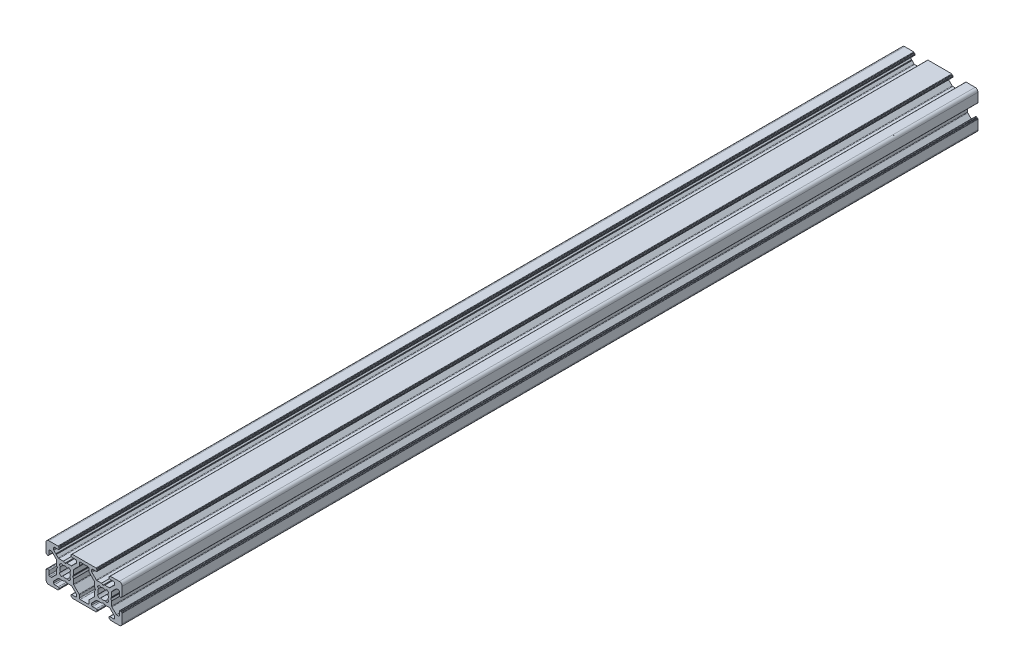
SolidWorks part; units mm, degrees
material "3.1355 (EN-AW 2024)"
ref_plane "Спереди" through (0, 0, 0) normal (0, 0, 1) x (1, 0, 0)
ref_plane "Сверху" through (0, 0, 0) normal (0, 1, 0) x (1, 0, 0)
ref_plane "Справа" through (0, 0, 0) normal (1, 0, 0) x (0, 0, -1)
sketch "Model" plane through (0, 0, 0) normal (0, 0, 1) x (1, 0, 0)
  line L0 (8.0901, 2.9922) -> (8.7418, 2.4453)
  line L1 (11.2582, 2.4453) -> (11.9099, 2.9922)
  line L2 (12.9896, 1.9139) -> (12.4453, 1.2582)
  line L3 (12.4453, -1.2582) -> (12.9896, -1.9139)
  line L4 (11.9099, -2.9922) -> (11.2582, -2.4453)
  line L5 (8.7418, -2.4453) -> (8.0901, -2.9922)
  line L6 (7.0104, -1.9139) -> (7.5547, -1.2582)
  line L7 (7.5547, 1.2582) -> (7.0104, 1.9139)
  line L8 (-7.0104, 1.9139) -> (-7.5547, 1.2582)
  line L9 (-7.5547, -1.2582) -> (-7.0104, -1.9139)
  line L10 (-8.0901, -2.9922) -> (-8.7418, -2.4453)
  line L11 (-11.2582, -2.4453) -> (-11.9099, -2.9922)
  line L12 (-12.9896, -1.9139) -> (-12.4453, -1.2582)
  line L13 (-12.4453, 1.2582) -> (-12.9896, 1.9139)
  line L14 (-11.9099, 2.9922) -> (-11.2582, 2.4453)
  line L15 (-8.7418, 2.4453) -> (-8.0901, 2.9922)
  line L16 (5.5267, 0.8538) -> (5.9619, 0.1)
  line L17 (5.9619, -0.1) -> (5.5267, -0.8538)
  line L18 (5.4999, -0.9538) -> (5.4999, -3.2324)
  line L19 (5.3534, -3.586) -> (2.6465, -6.2929)
  line L20 (2.5, -6.6464) -> (2.5, -8)
  line L21 (2, -8.5) -> (-2, -8.5)
  line L22 (-2.5, -8) -> (-2.5, -6.6464)
  line L23 (-2.6464, -6.2929) -> (-5.3535, -3.5858)
  line L24 (-5.5, -3.2322) -> (-5.5, -0.9536)
  line L25 (-5.5268, -0.8536) -> (-5.9619, -0.1)
  line L26 (-5.9619, 0.1) -> (-5.5268, 0.8536)
  line L27 (-5.5, 0.9536) -> (-5.5, 3.2322)
  line L28 (-5.3535, 3.5858) -> (-2.6464, 6.2929)
  line L29 (-2.5, 6.6464) -> (-2.5, 8)
  line L30 (-2, 8.5) -> (2, 8.5)
  line L31 (2.5, 8) -> (2.5, 6.6464)
  line L32 (2.6465, 6.2929) -> (5.3534, 3.586)
  line L33 (5.4999, 3.2324) -> (5.4999, 0.9538)
  line L34 (-14.7904, 5.7096) -> (-14.8421, 5.9028)
  line L35 (-14.8421, 5.9028) -> (-15.8536, 6.9142)
  line L36 (-16, 7.2678) -> (-16, 8)
  line L37 (-15.5, 8.5) -> (-13.6, 8.5)
  line L38 (-13.1, 9) -> (-13.1, 9.3)
  line L39 (-13.3, 9.5) -> (-13.35, 9.5)
  line L40 (-13.55, 9.7) -> (-13.55, 9.8)
  line L41 (-13.75, 10) -> (-18.5, 10)
  line L42 (-20, 8.5) -> (-20, 3.75)
  line L43 (-19.8, 3.55) -> (-19.7, 3.55)
  line L44 (-19.5, 3.35) -> (-19.5, 3.3)
  line L45 (-19.3, 3.1) -> (-19, 3.1)
  line L46 (-18.5, 3.6) -> (-18.5, 5.5)
  line L47 (-18, 6) -> (-17.2678, 6)
  line L48 (-16.9142, 5.8536) -> (-14.6464, 3.5858)
  line L49 (-14.5, 3.2322) -> (-14.5, 0.9536)
  line L50 (-14.4732, 0.8536) -> (-14.0381, 0.1)
  line L51 (-14.0381, -0.1) -> (-14.4732, -0.8536)
  line L52 (-14.5, -0.9536) -> (-14.5, -3.2322)
  line L53 (-14.6464, -3.5858) -> (-16.9142, -5.8536)
  line L54 (-17.2678, -6) -> (-18, -6)
  line L55 (-18.5, -5.5) -> (-18.5, -3.6)
  line L56 (-19, -3.1) -> (-19.3, -3.1)
  line L57 (-19.5, -3.3) -> (-19.5, -3.35)
  line L58 (-19.7, -3.55) -> (-19.8, -3.55)
  line L59 (-20, -3.75) -> (-20, -8.5)
  line L60 (-18.5, -10) -> (-13.75, -10)
  line L61 (-13.55, -9.8) -> (-13.55, -9.7)
  line L62 (-13.35, -9.5) -> (-13.3, -9.5)
  line L63 (-13.1, -9.3) -> (-13.1, -9)
  line L64 (-13.6, -8.5) -> (-15.5, -8.5)
  line L65 (-16, -8) -> (-16, -7.2678)
  line L66 (-15.8536, -6.9142) -> (-13.5858, -4.6464)
  line L67 (-13.2322, -4.5) -> (-10.9536, -4.5)
  line L68 (-10.8536, -4.4732) -> (-10.1, -4.0381)
  line L69 (-9.9, -4.0381) -> (-9.1464, -4.4732)
  line L70 (-9.0464, -4.5) -> (-6.7678, -4.5)
  line L71 (-6.4142, -4.6464) -> (-4.1464, -6.9142)
  line L72 (-4, -7.2678) -> (-4, -8)
  line L73 (-4.5, -8.5) -> (-6.4, -8.5)
  line L74 (-6.9, -9) -> (-6.9, -9.3)
  line L75 (-6.7, -9.5) -> (-6.65, -9.5)
  line L76 (-6.45, -9.7) -> (-6.45, -9.8)
  line L77 (-6.25, -10) -> (6.25, -10)
  line L78 (6.45, -9.8) -> (6.45, -9.7)
  line L79 (6.65, -9.5) -> (6.7, -9.5)
  line L80 (6.9, -9.3) -> (6.9, -9)
  line L81 (6.4, -8.5) -> (4.5, -8.5)
  line L82 (4, -8) -> (4, -7.2678)
  line L83 (4.1464, -6.9142) -> (6.4142, -4.6464)
  line L84 (6.7678, -4.5) -> (9.0464, -4.5)
  line L85 (9.1464, -4.4732) -> (9.9, -4.0381)
  line L86 (10.1, -4.0381) -> (10.8536, -4.4732)
  line L87 (10.9536, -4.5) -> (13.2322, -4.5)
  line L88 (13.5858, -4.6464) -> (15.8536, -6.9142)
  line L89 (16, -7.2678) -> (16, -8)
  line L90 (15.5, -8.5) -> (13.6, -8.5)
  line L91 (13.1, -9) -> (13.1, -9.3)
  line L92 (13.3, -9.5) -> (13.35, -9.5)
  line L93 (13.55, -9.7) -> (13.55, -9.8)
  line L94 (13.75, -10) -> (18.5, -10)
  line L95 (20, -8.5) -> (20, -3.75)
  line L96 (19.8, -3.55) -> (19.7, -3.55)
  line L97 (19.5, -3.35) -> (19.5, -3.3)
  line L98 (19.3, -3.1) -> (19, -3.1)
  line L99 (18.5, -3.6) -> (18.5, -5.5)
  line L100 (18, -6) -> (17.2678, -6)
  line L101 (16.9142, -5.8536) -> (14.6464, -3.5858)
  line L102 (14.5, -3.2322) -> (14.5, -0.9536)
  line L103 (14.4732, -0.8536) -> (14.0381, -0.1)
  line L104 (14.0381, 0.1) -> (14.4732, 0.8536)
  line L105 (14.5, 0.9536) -> (14.5, 3.2322)
  line L106 (14.6464, 3.5858) -> (16.9142, 5.8536)
  line L107 (17.2678, 6) -> (18, 6)
  line L108 (18.5, 5.5) -> (18.5, 3.6)
  line L109 (19, 3.1) -> (19.3, 3.1)
  line L110 (19.5, 3.3) -> (19.5, 3.35)
  line L111 (19.7, 3.55) -> (19.8, 3.55)
  line L112 (20, 3.75) -> (20, 8.5)
  line L113 (18.5, 10) -> (13.75, 10)
  line L114 (13.55, 9.8) -> (13.55, 9.7)
  line L115 (13.35, 9.5) -> (13.3, 9.5)
  line L116 (13.1, 9.3) -> (13.1, 9)
  line L117 (13.6, 8.5) -> (15.5, 8.5)
  line L118 (16, 8) -> (16, 7.2678)
  line L119 (15.8536, 6.9142) -> (13.5858, 4.6464)
  line L120 (13.2322, 4.5) -> (10.9536, 4.5)
  line L121 (10.8536, 4.4732) -> (10.1, 4.0381)
  line L122 (9.9, 4.0381) -> (9.1464, 4.4732)
  line L123 (9.0464, 4.5) -> (6.7678, 4.5)
  line L124 (6.4142, 4.6464) -> (4.1464, 6.9142)
  line L125 (4, 7.2678) -> (4, 8)
  line L126 (4.5, 8.5) -> (6.4, 8.5)
  line L127 (6.9, 9) -> (6.9, 9.3)
  line L128 (6.7, 9.5) -> (6.65, 9.5)
  line L129 (6.45, 9.7) -> (6.45, 9.8)
  line L130 (6.25, 10) -> (-6.25, 10)
  line L131 (-6.45, 9.8) -> (-6.45, 9.7)
  line L132 (-6.65, 9.5) -> (-6.7, 9.5)
  line L133 (-6.9, 9.3) -> (-6.9, 9)
  line L134 (-6.4, 8.5) -> (-4.5, 8.5)
  line L135 (-4, 8) -> (-4, 7.2678)
  line L136 (-4.1464, 6.9142) -> (-6.4142, 4.6464)
  line L137 (-6.7678, 4.5) -> (-9.0464, 4.5)
  line L138 (-9.1464, 4.4732) -> (-9.9, 4.0381)
  line L139 (-10.1, 4.0381) -> (-10.8536, 4.4732)
  line L140 (-10.9536, 4.5) -> (-13.2322, 4.5)
  line L141 (-13.5858, 4.6464) -> (-14.5972, 5.6579)
  line L142 (-14.5972, 5.6579) -> (-14.7904, 5.7096)
  arc A0 (8.0901, 2.9922) -> (7.0104, 1.9139) centre (10, 0) ccw
  arc A1 (11.2582, 2.4453) -> (8.7418, 2.4453) centre (10, 0) ccw
  arc A2 (12.9896, 1.9139) -> (11.9099, 2.9922) centre (10, 0) ccw
  arc A3 (12.4453, -1.2582) -> (12.4453, 1.2582) centre (10, 0) ccw
  arc A4 (11.9099, -2.9922) -> (12.9896, -1.9139) centre (10, 0) ccw
  arc A5 (8.7418, -2.4453) -> (11.2582, -2.4453) centre (10, 0) ccw
  arc A6 (7.0104, -1.9139) -> (8.0901, -2.9922) centre (10, 0) ccw
  arc A7 (7.5547, 1.2582) -> (7.5547, -1.2582) centre (10, 0) ccw
  arc A8 (-7.0104, 1.9139) -> (-8.0901, 2.9922) centre (-10, 0) ccw
  arc A9 (-7.5547, -1.2582) -> (-7.5547, 1.2582) centre (-10, 0) ccw
  arc A10 (-8.0901, -2.9922) -> (-7.0104, -1.9139) centre (-10, 0) ccw
  arc A11 (-11.2582, -2.4453) -> (-8.7418, -2.4453) centre (-10, 0) ccw
  arc A12 (-12.9896, -1.9139) -> (-11.9099, -2.9922) centre (-10, 0) ccw
  arc A13 (-12.4453, 1.2582) -> (-12.4453, -1.2582) centre (-10, 0) ccw
  arc A14 (-11.9099, 2.9922) -> (-12.9896, 1.9139) centre (-10, 0) ccw
  arc A15 (-8.7418, 2.4453) -> (-11.2582, 2.4453) centre (-10, 0) ccw
  arc A16 (5.9619, -0.1) -> (5.9619, 0.1) centre (5.7887, 0) ccw
  arc A17 (5.5267, -0.8538) -> (5.4999, -0.9538) centre (5.6999, -0.9538) ccw
  arc A18 (5.3534, -3.586) -> (5.4999, -3.2324) centre (4.9999, -3.2324) ccw
  arc A19 (2.6465, -6.2929) -> (2.5, -6.6464) centre (3, -6.6464) ccw
  arc A20 (2, -8.5) -> (2.5, -8) centre (2, -8) ccw
  arc A21 (-2.5, -8) -> (-2, -8.5) centre (-2, -8) ccw
  arc A22 (-2.5, -6.6464) -> (-2.6464, -6.2929) centre (-3, -6.6464) ccw
  arc A23 (-5.5, -3.2322) -> (-5.3535, -3.5858) centre (-5, -3.2322) ccw
  arc A24 (-5.5, -0.9536) -> (-5.5268, -0.8536) centre (-5.7, -0.9536) ccw
  arc A25 (-5.9619, 0.1) -> (-5.9619, -0.1) centre (-5.7887, 0) ccw
  arc A26 (-5.5268, 0.8536) -> (-5.5, 0.9536) centre (-5.7, 0.9536) ccw
  arc A27 (-5.3535, 3.5858) -> (-5.5, 3.2322) centre (-5, 3.2322) ccw
  arc A28 (-2.6464, 6.2929) -> (-2.5, 6.6464) centre (-3, 6.6464) ccw
  arc A29 (-2, 8.5) -> (-2.5, 8) centre (-2, 8) ccw
  arc A30 (2.5, 8) -> (2, 8.5) centre (2, 8) ccw
  arc A31 (2.5, 6.6464) -> (2.6465, 6.2929) centre (3, 6.6464) ccw
  arc A32 (5.4999, 3.2324) -> (5.3534, 3.586) centre (4.9999, 3.2324) ccw
  arc A33 (5.4999, 0.9538) -> (5.5267, 0.8538) centre (5.6999, 0.9538) ccw
  arc A34 (-16, 7.2678) -> (-15.8536, 6.9142) centre (-15.5, 7.2678) ccw
  arc A35 (-15.5, 8.5) -> (-16, 8) centre (-15.5, 8) ccw
  arc A36 (-13.6, 8.5) -> (-13.1, 9) centre (-13.6, 9) ccw
  arc A37 (-13.1, 9.3) -> (-13.3, 9.5) centre (-13.3, 9.3) ccw
  arc A38 (-13.55, 9.7) -> (-13.35, 9.5) centre (-13.35, 9.7) ccw
  arc A39 (-13.55, 9.8) -> (-13.75, 10) centre (-13.75, 9.8) ccw
  arc A40 (-18.5, 10) -> (-20, 8.5) centre (-18.5, 8.5) ccw
  arc A41 (-20, 3.75) -> (-19.8, 3.55) centre (-19.8, 3.75) ccw
  arc A42 (-19.5, 3.35) -> (-19.7, 3.55) centre (-19.7, 3.35) ccw
  arc A43 (-19.5, 3.3) -> (-19.3, 3.1) centre (-19.3, 3.3) ccw
  arc A44 (-19, 3.1) -> (-18.5, 3.6) centre (-19, 3.6) ccw
  arc A45 (-18, 6) -> (-18.5, 5.5) centre (-18, 5.5) ccw
  arc A46 (-16.9142, 5.8536) -> (-17.2678, 6) centre (-17.2678, 5.5) ccw
  arc A47 (-14.5, 3.2322) -> (-14.6464, 3.5858) centre (-15, 3.2322) ccw
  arc A48 (-14.5, 0.9536) -> (-14.4732, 0.8536) centre (-14.3, 0.9536) ccw
  arc A49 (-14.0381, -0.1) -> (-14.0381, 0.1) centre (-14.2113, 0) ccw
  arc A50 (-14.4732, -0.8536) -> (-14.5, -0.9536) centre (-14.3, -0.9536) ccw
  arc A51 (-14.6464, -3.5858) -> (-14.5, -3.2322) centre (-15, -3.2322) ccw
  arc A52 (-17.2678, -6) -> (-16.9142, -5.8536) centre (-17.2678, -5.5) ccw
  arc A53 (-18.5, -5.5) -> (-18, -6) centre (-18, -5.5) ccw
  arc A54 (-18.5, -3.6) -> (-19, -3.1) centre (-19, -3.6) ccw
  arc A55 (-19.3, -3.1) -> (-19.5, -3.3) centre (-19.3, -3.3) ccw
  arc A56 (-19.7, -3.55) -> (-19.5, -3.35) centre (-19.7, -3.35) ccw
  arc A57 (-19.8, -3.55) -> (-20, -3.75) centre (-19.8, -3.75) ccw
  arc A58 (-20, -8.5) -> (-18.5, -10) centre (-18.5, -8.5) ccw
  arc A59 (-13.75, -10) -> (-13.55, -9.8) centre (-13.75, -9.8) ccw
  arc A60 (-13.35, -9.5) -> (-13.55, -9.7) centre (-13.35, -9.7) ccw
  arc A61 (-13.3, -9.5) -> (-13.1, -9.3) centre (-13.3, -9.3) ccw
  arc A62 (-13.1, -9) -> (-13.6, -8.5) centre (-13.6, -9) ccw
  arc A63 (-16, -8) -> (-15.5, -8.5) centre (-15.5, -8) ccw
  arc A64 (-15.8536, -6.9142) -> (-16, -7.2678) centre (-15.5, -7.2678) ccw
  arc A65 (-13.2322, -4.5) -> (-13.5858, -4.6464) centre (-13.2322, -5) ccw
  arc A66 (-10.9536, -4.5) -> (-10.8536, -4.4732) centre (-10.9536, -4.3) ccw
  arc A67 (-9.9, -4.0381) -> (-10.1, -4.0381) centre (-10, -4.2113) ccw
  arc A68 (-9.1464, -4.4732) -> (-9.0464, -4.5) centre (-9.0464, -4.3) ccw
  arc A69 (-6.4142, -4.6464) -> (-6.7678, -4.5) centre (-6.7678, -5) ccw
  arc A70 (-4, -7.2678) -> (-4.1464, -6.9142) centre (-4.5, -7.2678) ccw
  arc A71 (-4.5, -8.5) -> (-4, -8) centre (-4.5, -8) ccw
  arc A72 (-6.4, -8.5) -> (-6.9, -9) centre (-6.4, -9) ccw
  arc A73 (-6.9, -9.3) -> (-6.7, -9.5) centre (-6.7, -9.3) ccw
  arc A74 (-6.45, -9.7) -> (-6.65, -9.5) centre (-6.65, -9.7) ccw
  arc A75 (-6.45, -9.8) -> (-6.25, -10) centre (-6.25, -9.8) ccw
  arc A76 (6.25, -10) -> (6.45, -9.8) centre (6.25, -9.8) ccw
  arc A77 (6.65, -9.5) -> (6.45, -9.7) centre (6.65, -9.7) ccw
  arc A78 (6.7, -9.5) -> (6.9, -9.3) centre (6.7, -9.3) ccw
  arc A79 (6.9, -9) -> (6.4, -8.5) centre (6.4, -9) ccw
  arc A80 (4, -8) -> (4.5, -8.5) centre (4.5, -8) ccw
  arc A81 (4.1464, -6.9142) -> (4, -7.2678) centre (4.5, -7.2678) ccw
  arc A82 (6.7678, -4.5) -> (6.4142, -4.6464) centre (6.7678, -5) ccw
  arc A83 (9.0464, -4.5) -> (9.1464, -4.4732) centre (9.0464, -4.3) ccw
  arc A84 (10.1, -4.0381) -> (9.9, -4.0381) centre (10, -4.2113) ccw
  arc A85 (10.8536, -4.4732) -> (10.9536, -4.5) centre (10.9536, -4.3) ccw
  arc A86 (13.5858, -4.6464) -> (13.2322, -4.5) centre (13.2322, -5) ccw
  arc A87 (16, -7.2678) -> (15.8536, -6.9142) centre (15.5, -7.2678) ccw
  arc A88 (15.5, -8.5) -> (16, -8) centre (15.5, -8) ccw
  arc A89 (13.6, -8.5) -> (13.1, -9) centre (13.6, -9) ccw
  arc A90 (13.1, -9.3) -> (13.3, -9.5) centre (13.3, -9.3) ccw
  arc A91 (13.55, -9.7) -> (13.35, -9.5) centre (13.35, -9.7) ccw
  arc A92 (13.55, -9.8) -> (13.75, -10) centre (13.75, -9.8) ccw
  arc A93 (18.5, -10) -> (20, -8.5) centre (18.5, -8.5) ccw
  arc A94 (20, -3.75) -> (19.8, -3.55) centre (19.8, -3.75) ccw
  arc A95 (19.5, -3.35) -> (19.7, -3.55) centre (19.7, -3.35) ccw
  arc A96 (19.5, -3.3) -> (19.3, -3.1) centre (19.3, -3.3) ccw
  arc A97 (19, -3.1) -> (18.5, -3.6) centre (19, -3.6) ccw
  arc A98 (18, -6) -> (18.5, -5.5) centre (18, -5.5) ccw
  arc A99 (16.9142, -5.8536) -> (17.2678, -6) centre (17.2678, -5.5) ccw
  arc A100 (14.5, -3.2322) -> (14.6464, -3.5858) centre (15, -3.2322) ccw
  arc A101 (14.5, -0.9536) -> (14.4732, -0.8536) centre (14.3, -0.9536) ccw
  arc A102 (14.0381, 0.1) -> (14.0381, -0.1) centre (14.2113, 0) ccw
  arc A103 (14.4732, 0.8536) -> (14.5, 0.9536) centre (14.3, 0.9536) ccw
  arc A104 (14.6464, 3.5858) -> (14.5, 3.2322) centre (15, 3.2322) ccw
  arc A105 (17.2678, 6) -> (16.9142, 5.8536) centre (17.2678, 5.5) ccw
  arc A106 (18.5, 5.5) -> (18, 6) centre (18, 5.5) ccw
  arc A107 (18.5, 3.6) -> (19, 3.1) centre (19, 3.6) ccw
  arc A108 (19.3, 3.1) -> (19.5, 3.3) centre (19.3, 3.3) ccw
  arc A109 (19.7, 3.55) -> (19.5, 3.35) centre (19.7, 3.35) ccw
  arc A110 (19.8, 3.55) -> (20, 3.75) centre (19.8, 3.75) ccw
  arc A111 (20, 8.5) -> (18.5, 10) centre (18.5, 8.5) ccw
  arc A112 (13.75, 10) -> (13.55, 9.8) centre (13.75, 9.8) ccw
  arc A113 (13.35, 9.5) -> (13.55, 9.7) centre (13.35, 9.7) ccw
  arc A114 (13.3, 9.5) -> (13.1, 9.3) centre (13.3, 9.3) ccw
  arc A115 (13.1, 9) -> (13.6, 8.5) centre (13.6, 9) ccw
  arc A116 (16, 8) -> (15.5, 8.5) centre (15.5, 8) ccw
  arc A117 (15.8536, 6.9142) -> (16, 7.2678) centre (15.5, 7.2678) ccw
  arc A118 (13.2322, 4.5) -> (13.5858, 4.6464) centre (13.2322, 5) ccw
  arc A119 (10.9536, 4.5) -> (10.8536, 4.4732) centre (10.9536, 4.3) ccw
  arc A120 (9.9, 4.0381) -> (10.1, 4.0381) centre (10, 4.2113) ccw
  arc A121 (9.1464, 4.4732) -> (9.0464, 4.5) centre (9.0464, 4.3) ccw
  arc A122 (6.4142, 4.6464) -> (6.7678, 4.5) centre (6.7678, 5) ccw
  arc A123 (4, 7.2678) -> (4.1464, 6.9142) centre (4.5, 7.2678) ccw
  arc A124 (4.5, 8.5) -> (4, 8) centre (4.5, 8) ccw
  arc A125 (6.4, 8.5) -> (6.9, 9) centre (6.4, 9) ccw
  arc A126 (6.9, 9.3) -> (6.7, 9.5) centre (6.7, 9.3) ccw
  arc A127 (6.45, 9.7) -> (6.65, 9.5) centre (6.65, 9.7) ccw
  arc A128 (6.45, 9.8) -> (6.25, 10) centre (6.25, 9.8) ccw
  arc A129 (-6.25, 10) -> (-6.45, 9.8) centre (-6.25, 9.8) ccw
  arc A130 (-6.65, 9.5) -> (-6.45, 9.7) centre (-6.65, 9.7) ccw
  arc A131 (-6.7, 9.5) -> (-6.9, 9.3) centre (-6.7, 9.3) ccw
  arc A132 (-6.9, 9) -> (-6.4, 8.5) centre (-6.4, 9) ccw
  arc A133 (-4, 8) -> (-4.5, 8.5) centre (-4.5, 8) ccw
  arc A134 (-4.1464, 6.9142) -> (-4, 7.2678) centre (-4.5, 7.2678) ccw
  arc A135 (-6.7678, 4.5) -> (-6.4142, 4.6464) centre (-6.7678, 5) ccw
  arc A136 (-9.0464, 4.5) -> (-9.1464, 4.4732) centre (-9.0464, 4.3) ccw
  arc A137 (-10.1, 4.0381) -> (-9.9, 4.0381) centre (-10, 4.2113) ccw
  arc A138 (-10.8536, 4.4732) -> (-10.9536, 4.5) centre (-10.9536, 4.3) ccw
  arc A139 (-13.5858, 4.6464) -> (-13.2322, 4.5) centre (-13.2322, 5) ccw
  dimension "D1" = 20
extrude "База" add sketch "Model" along normal mid plane 449.5
